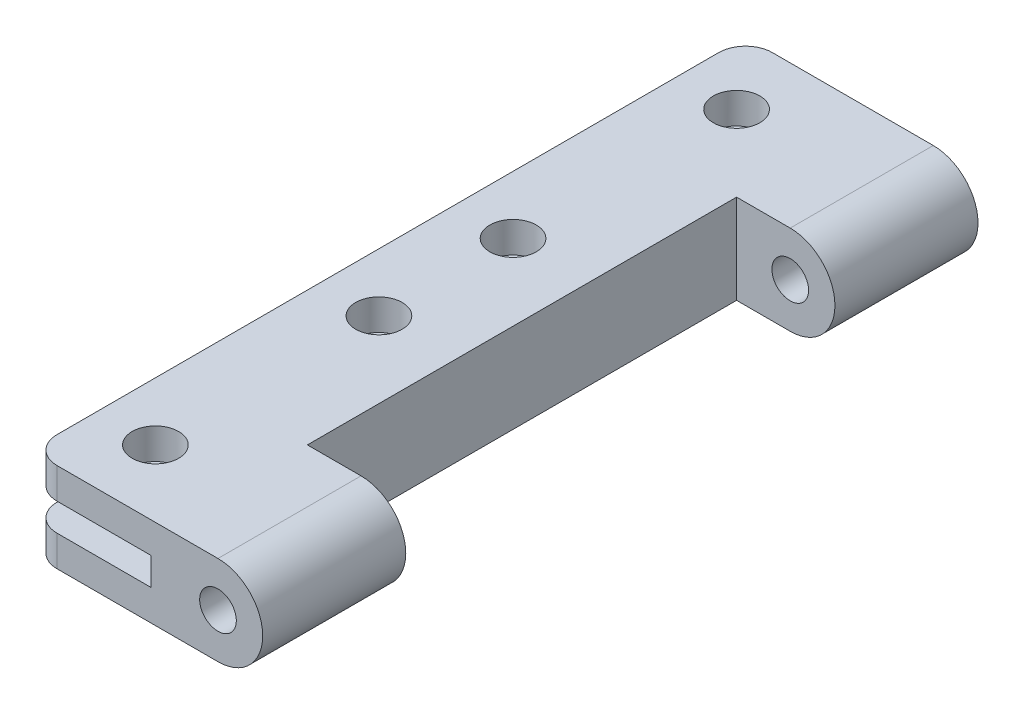
SolidWorks part; units mm, degrees
ref_plane "前视基准面" through (0, 0, 0) normal (0, 0, 1) x (1, 0, 0)
ref_plane "上视基准面" through (0, 0, 0) normal (0, 1, 0) x (1, 0, 0)
ref_plane "右视基准面" through (0, 0, 0) normal (1, 0, 0) x (0, 0, -1)
sketch "草图1" plane through (0, 0, 0) normal (0, 0, 1) x (1, 0, 0)
  line L0 (-228.2325, 0) -> (11183.3925, 0) construction
  line L1 (0, -228.2325) -> (0, 11183.3925) construction
  line L2 (0, 5) -> (21, 5)
  line L3 (21, -5) -> (0, -5)
  line L4 (0, -5) -> (0, 5)
  line L5 (21, -1005) -> (21, 48995) construction
  arc A0 (21, 5) -> (21, -5) centre (21, 0) cw
  circle A2 centre (21, 0) radius 2.05
  dimension "D1" = 4.1
  dimension "D2" = 5
  dimension "D4" = 5
  dimension "D3" = 0
  dimension "D5" = 21
extrude "凸台-拉伸1" add sketch "草图1" along normal blind 80
sketch "草图2" plane through (0, 0, 80) normal (0, 0, 1) x (1, 0, 0)
  line L0 (0, 1.55) -> (13.5, 1.55)
  line L1 (0, 5) -> (0, -5) construction
  line L2 (13.5, 1.55) -> (13.5, -1.55)
  line L3 (13.5, -1.55) -> (0, -1.55)
  line L4 (0, -1.55) -> (0, 1.55)
  line L5 (-1000, 0) -> (49000, 0) construction
  dimension "D1" = 3.1
  dimension "D2" = 13.5
extrude "切除-拉伸1" cut sketch "草图2" against normal blind 95
sketch "草图4" plane through (0, 5, 0) normal (0, 1, 0) x (1, 0, 0)
  line L0 (0, -80) -> (0, 0) construction
  line L1 (21, -80) -> (21, 0) construction
  line L2 (-985, -40) -> (49015, -40) construction
  circle A2 centre (6.5, -32.5) radius 2.6
  circle A3 centre (6.5, -7.5) radius 2.6
  circle A4 centre (6.5, -72.5) radius 2.6
  circle A5 centre (6.5, -47.5) radius 2.6
  point P11 (21, -40)
  dimension "D2" = 6.5
  dimension "D3" = 5.2
  dimension "D4" = 6.5
  dimension "D1" = 7.5
  dimension "D5" = 25
extrude "切除-拉伸2" cut sketch "草图4" against normal blind 20
sketch "草图5" plane through (0, 5, 0) normal (0, 1, 0) x (1, 0, 0)
  line L0 (-989.0255, -40) -> (49010.9745, -40) construction
  line L1 (21, -80) -> (21, 0) construction
  line L2 (21, -1016) -> (21, 48984) construction
  line L7 (21, 984) -> (21, -49016) construction
  line L19 (15, -16) -> (15, -64)
  line L28 (47.1159, -64) -> (47.1159, -16)
  line L29 (47.1159, -16) -> (15, -16)
  line L30 (15, -64) -> (47.1159, -64)
  line L31 (21, 0) -> (0, 0) construction
  line L32 (21, -80) -> (26, -80) construction
  point P5 (21, -40)
  point P16 (47.1159, -40)
  point P17 (21, -40)
  point P19 (13.261, -40)
  dimension "D1" = 16
  dimension "D2" = 16
ref_plane "基准面4" through (13.5, 1.55, 0) normal (0, 0, 1) x (1, 0, 0)
extrude "切除-拉伸5" cut sketch "草图5" against normal blind 20
ref_plane "基准面5" through (21, -5, 80) normal (0, 0, -1) x (-1, 0, 0)
fillet "圆角1" radius 3 4 edges at (0, -3.275, 80) (0, 3.275, 80) (0, -3.275, 0) (0, 3.275, 0)
